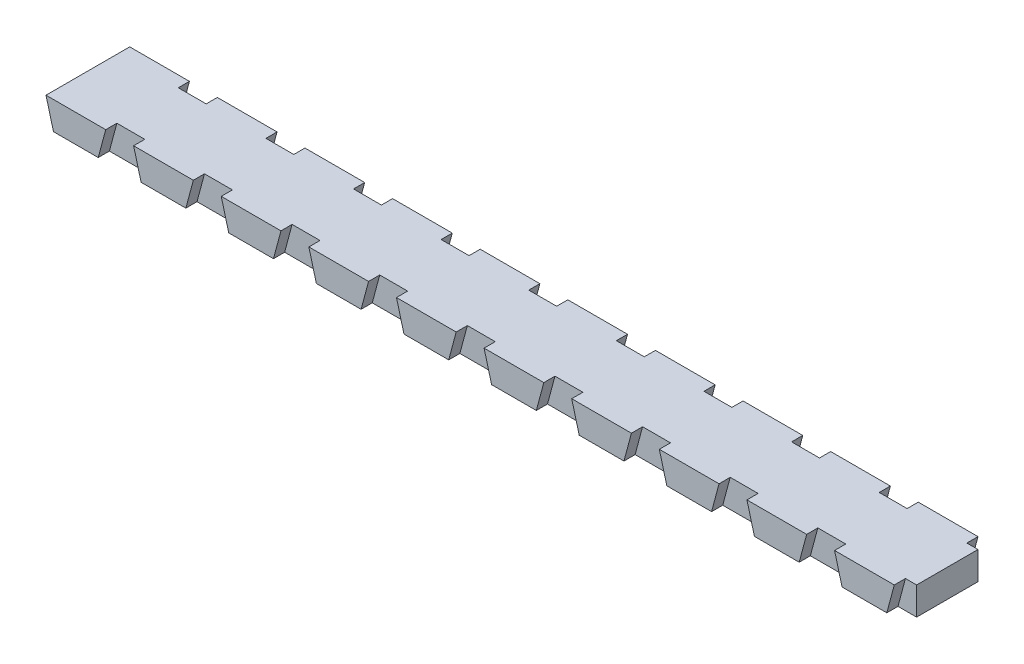
SolidWorks part; units mm, degrees
ref_plane "Front Plane" through (0, 0, 0) normal (0, 0, 1) x (1, 0, 0)
ref_plane "Top Plane" through (0, 0, 0) normal (0, 1, 0) x (1, 0, 0)
ref_plane "Right Plane" through (0, 0, 0) normal (1, 0, 0) x (0, 0, -1)
sketch "Sketch2" plane through (0, 0, 0) normal (0, 1, 0) x (1, 0, 0)
  line L1 (-770, 55) -> (770, 55)
  line L2 (-770, 55) -> (-770, -55)
  line L3 (-770, -55) -> (770, -55)
  line L4 (770, 55) -> (770, -55)
  line L5 (-770, 55) -> (770, -55) construction
  line L6 (-770, -55) -> (770, 55) construction
  point P0 (0, 0)
  dimension "D1" = 110
  dimension "D2" = 1540
extrude "Boss-Extrude1" add sketch "Sketch2" along normal blind 50
sketch "Sketch3" plane through (0, 50, 0) normal (0, 1, 0) x (1, 0, 0)
  line L0 (-770, 55) -> (-770, 75)
  line L1 (-770, 75) -> (-663, 75)
  line L2 (-663, 75) -> (-663, 55)
  line L3 (770, 55) -> (-770, 55) construction
  dimension "D1" = 20
  dimension "D2" = 107
sketch "Sketch4" plane through (0, 0, -55) normal (0, 0, -1) x (-1, 0, 0)
  line L0 (663, 50) -> (676.3975, 0)
  line L1 (-770, 0) -> (770, 0) construction
  line L2 (676.3975, 0) -> (756.6025, 0)
  line L3 (756.6025, 0) -> (770, 50)
  line L4 (-770, 50) -> (770, 50) construction
  line L5 (663, 50) -> (770, 50)
  dimension "D1" = 75
  dimension "D2" = 75
extrude "Boss-Extrude3" add sketch "Sketch4" along normal blind 20
pattern_linear "LPattern1" count 10 spacing 157 along (1, 0, 0) of "Boss-Extrude3"
ref_plane "Plane2" through (0, 0, 0) normal (0, 0, -1) x (-1, 0, 0)
mirror "Mirror2" about plane through (0, 0, 0) normal (0, 0, -1) of "LPattern1", "Boss-Extrude3"
